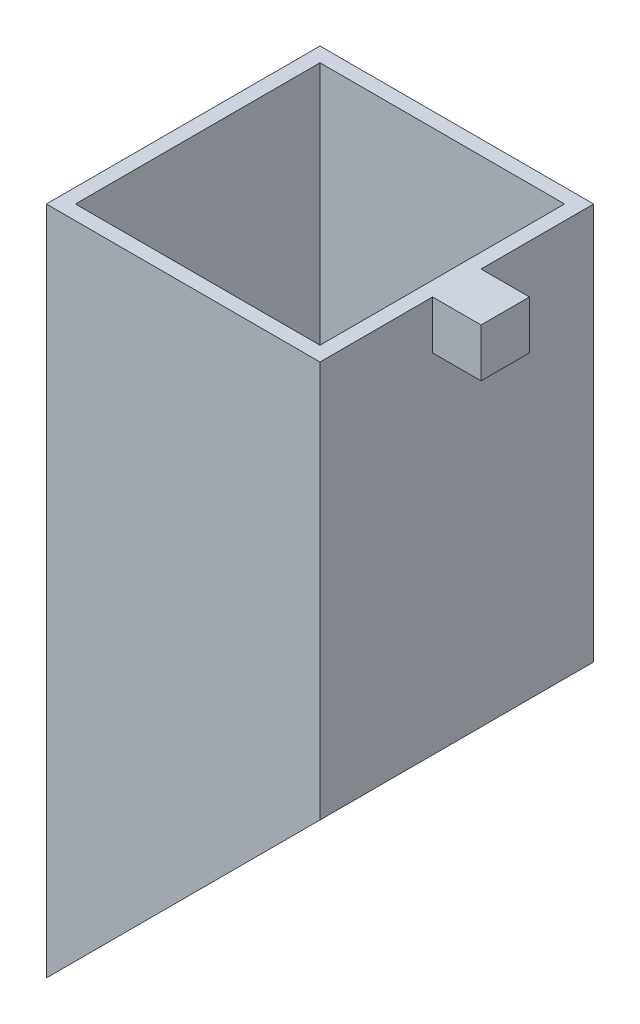
SolidWorks part; units mm, degrees
ref_plane "Alzado" through (0, 0, 0) normal (0, 0, 1) x (1, 0, 0)
ref_plane "Planta" through (0, 0, 0) normal (0, 1, 0) x (1, 0, 0)
ref_plane "Vista lateral" through (0, 0, 0) normal (1, 0, 0) x (0, 0, -1)
sketch "Croquis1" plane through (0, 0, 0) normal (0, 1, 0) x (1, 0, 0)
  line L1 (0, 0) -> (56.5, 0)
  line L2 (0, 0) -> (0, 56.5)
  line L3 (0, 56.5) -> (56.5, 56.5)
  line L4 (56.5, 0) -> (56.5, 56.5)
  dimension "D1" = 56.5
  dimension "D2" = 56.5
extrude "Saliente-Extruir1" add sketch "Croquis1" along normal blind 81.9
sketch "Croquis2" plane through (0, 0, 0) normal (0, 0, 1) x (1, 0, 0)
  line L0 (0, 0) -> (0, -56.5)
  line L1 (0, -56.5) -> (56.5, 0)
  line L2 (56.5, 0) -> (0, 0)
  dimension "D1" = 45
extrude "Saliente-Extruir2" add sketch "Croquis2" against normal up to surface (56.5 mm away) up to face at (28.25, 40.95, -56.5)
shell "Vaciado4" thickness 3
sketch "Croquis3" plane through (0, 81.9, 0) normal (0, 1, 0) x (1, 0, 0)
  line L0 (56.5, 0) -> (56.5, 56.5) construction
  line L1 (66.5, 33.25) -> (56.5, 33.25)
  line L2 (66.5, 33.25) -> (66.5, 23.25)
  line L3 (66.5, 23.25) -> (56.5, 23.25)
  line L4 (56.5, 33.25) -> (56.5, 23.25)
  line L5 (66.5, 33.25) -> (56.5, 23.25) construction
  line L6 (66.5, 23.25) -> (56.5, 33.25) construction
  point P0 (61.5, 28.25)
  point P7 (56.5, 28.25)
  dimension "D1" = 10
  dimension "D2" = 10
extrude "Saliente-Extruir3" add sketch "Croquis3" against normal blind 10
